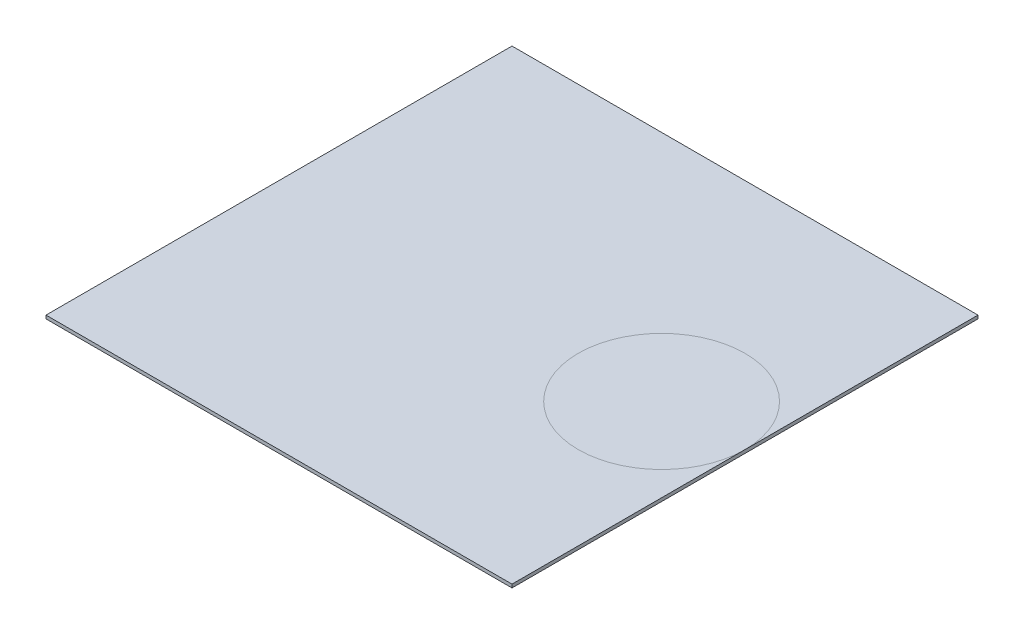
SolidWorks part; units mm, degrees
material "Zirconia"
ref_plane "Front Plane" through (0, 0, 0) normal (0, 0, 1) x (1, 0, 0)
ref_plane "Top Plane" through (0, 0, 0) normal (0, 1, 0) x (1, 0, 0)
ref_plane "Right Plane" through (0, 0, 0) normal (1, 0, 0) x (0, 0, -1)
sketch "Sketch1" plane through (0, 0, 0) normal (0, 1, 0) x (1, 0, 0)
  line L1 (-69.85, -69.85) -> (69.85, -69.85)
  line L2 (-69.85, -69.85) -> (-69.85, 69.85)
  line L3 (-69.85, 69.85) -> (69.85, 69.85)
  line L4 (69.85, -69.85) -> (69.85, 69.85)
  line L5 (-69.85, -69.85) -> (69.85, 69.85) construction
  line L6 (-69.85, 69.85) -> (69.85, -69.85) construction
  point P0 (0, 0)
  dimension "D1" = 139.7
extrude "Boss-Extrude1" add sketch "Sketch1" along normal mid plane 1
sketch "Sketch2" plane through (0, 0.5, 0) normal (0, 1, 0) x (1, 0, 0)
  line L0 (0, 0) -> (44.85, 0) construction
  line L1 (69.85, -69.85) -> (69.85, 69.85) construction
  circle A1 centre (44.85, 0) radius 25
  dimension "D1" = 50
split line "Split Line1"
equation "\"panel_width\"= 5.5in"
equation "\"finger_joint_width\" = 30mm"
equation "\"D1@Sketch1\"=\"panel_width\""
